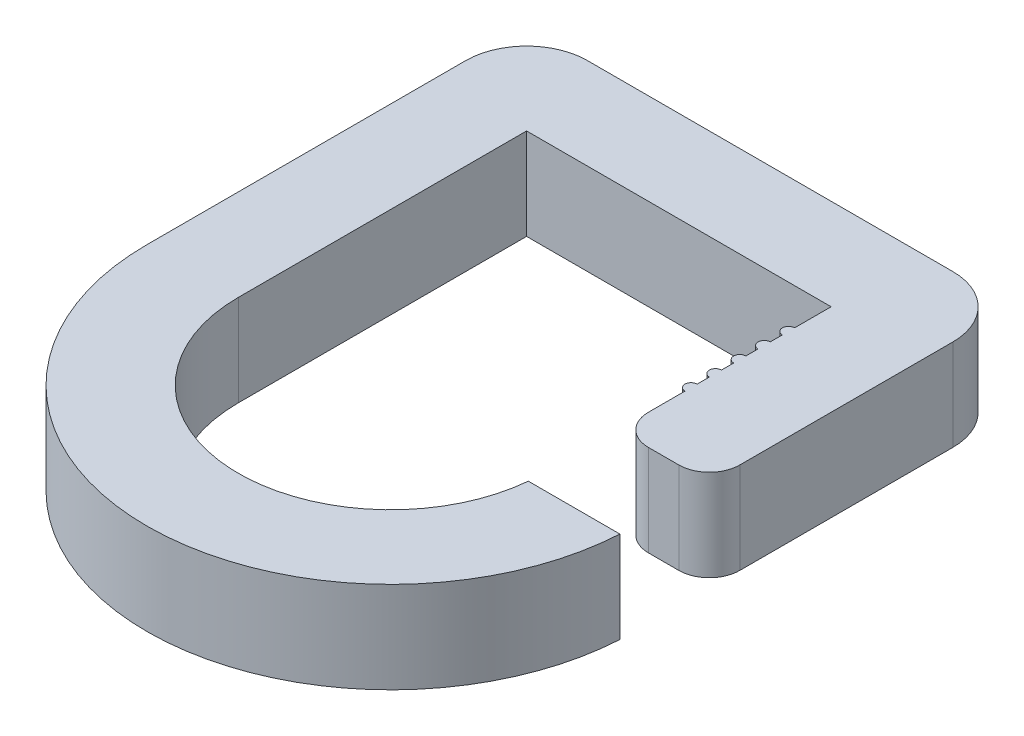
SolidWorks part; units mm, degrees
ref_plane "Front Plane" through (0, 0, 0) normal (0, 0, 1) x (1, 0, 0)
ref_plane "Top Plane" through (0, 0, 0) normal (0, 1, 0) x (1, 0, 0)
ref_plane "Right Plane" through (0, 0, 0) normal (1, 0, 0) x (0, 0, -1)
sketch "Sketch2" plane through (0, 0, 0) normal (0, 1, 0) x (1, 0, 0)
  line L0 (64.938, -49.6596) -> (79.9787, -49.6596)
  line L1 (15, 0) -> (65, 0)
  line L2 (0, 0) -> (0, 15)
  line L3 (0, 15) -> (80, 15)
  line L4 (80, 0) -> (80, 15)
  line L6 (0, 0) -> (0, -47.3315)
  line L8 (15, 0) -> (15, -47.3315)
  line L10 (65, 0) -> (65, -35)
  line L11 (65, -35) -> (80, -35)
  line L12 (80, 0) -> (80, -35)
  arc A0 (0, -47.3315) -> (79.9787, -49.6596) centre (40.0232, -47.3315) ccw
  arc A1 (15, -47.3315) -> (64.938, -49.6596) centre (40.0232, -47.3315) ccw
  dimension "D6" = 15
  dimension "D1" = 80
  dimension "D2" = 15
  dimension "D3" = 15
  dimension "D4" = 15
extrude "Boss-Extrude1" add sketch "Sketch2" along normal blind 15
fillet "Fillet2" radius 10 2 edges at (80, 7.5, -15) (0, 7.5, -15)
fillet "Fillet3" radius 5 2 edges at (65, 7.5, 35) (80, 7.5, 35)
sketch "Sketch3" plane through (0, 15, 0) normal (0, 1, 0) x (1, 0, 0)
  line L0 (65, 0) -> (65, -30) construction
  circle A0 centre (65, -15) radius 1
  circle A1 centre (65, -11) radius 1
  circle A2 centre (65, -23) radius 1
  circle A3 centre (65, -19) radius 1
  circle A4 centre (65, -7) radius 1
  dimension "D1" = 2
  dimension "D2" = 2
  dimension "D3" = 2
  dimension "D4" = 2
  dimension "D8" = 2
  dimension "D5" = 4
  dimension "D6" = 4
  dimension "D7" = 4
  dimension "D9" = 4
extrude "Boss-Extrude2" add sketch "Sketch3" against normal up to surface (15 mm away) up to face at (49.1196, 0, 24.6132)
